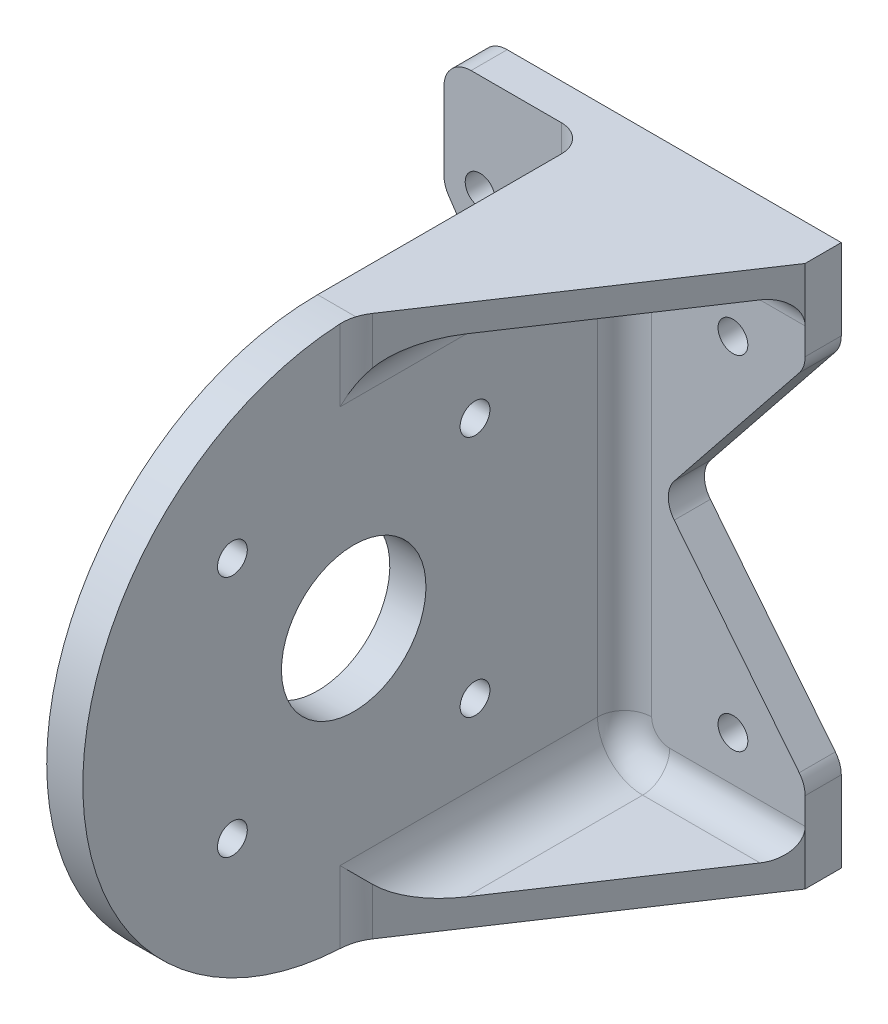
SolidWorks part; units mm, degrees
ref_plane "前视基准面" through (0, 0, 0) normal (0, 0, 1) x (1, 0, 0)
ref_plane "上视基准面" through (0, 0, 0) normal (0, 1, 0) x (1, 0, 0)
ref_plane "右视基准面" through (0, 0, 0) normal (1, 0, 0) x (0, 0, -1)
sketch "草图3" plane through (0, 0, 0) normal (0, 0, 1) x (1, 0, 0)
  line L6 (10, -30) -> (-10, -30)
  line L7 (10, -30) -> (10, 30)
  line L8 (10, 30) -> (-10, 30)
  line L9 (-10, -30) -> (-10, 30)
  line L10 (0, 30) -> (0, -30) construction
  line L11 (10, 0) -> (-10, 0) construction
  point P0 (0, 0)
  dimension "D1" = 20
  dimension "D2" = 60
extrude "凸台-拉伸2" add sketch "草图3" along normal blind 4 separate body
sketch "草图4" plane through (10, 0, 0) normal (1, 0, 0) x (0, 0, -1)
  line L0 (0, 30) -> (-34, 30)
  line L1 (0, -30) -> (-34, -30)
  line L2 (0, -30) -> (0, 30) construction
  line L3 (0, -30) -> (0, 30)
  line L4 (-34, 70) -> (-34, -49930) construction
  line L5 (-39, 0) -> (-50039, 0) construction
  line L7 (-47.435, 13.435) -> (-20.565, 13.435) construction
  line L8 (-47.435, 13.435) -> (-47.435, -13.435) construction
  line L9 (-47.435, -13.435) -> (-20.565, -13.435) construction
  line L10 (-20.565, 13.435) -> (-20.565, -13.435) construction
  line L11 (-34, -13.435) -> (-34, 13.435) construction
  line L12 (-47.435, 0) -> (-20.565, 0) construction
  arc A0 (-34, 30) -> (-34, -30) centre (-34, 0) ccw
  circle A1 centre (-34, 0) radius 8
  circle A2 centre (-47.435, 13.435) radius 1.65
  circle A3 centre (-20.565, 13.435) radius 1.65
  circle A4 centre (-20.565, -13.435) radius 1.65
  circle A5 centre (-47.435, -13.435) radius 1.65
  point P11 (-64, 0)
  dimension "D2" = 16
  dimension "D3" = 3.3
  dimension "D1" = 34
  dimension "D4" = 38
extrude "凸台-拉伸3" add sketch "草图4" against normal blind 4
sketch "草图9" plane through (0, 0, 0) normal (0, 0, 1) x (1, 0, 0)
  line L0 (10, -30) -> (10, 30) construction
  line L1 (10, 30) -> (30, 30)
  line L2 (10, 30) -> (10, -30)
  line L3 (10, -30) -> (30, -30)
  line L4 (30, 30) -> (30, -30)
  line L5 (6, 30) -> (-10, 30) construction
  line L6 (-10, -30) -> (6, -30) construction
  dimension "D1" = 20
extrude "凸台-拉伸6" add sketch "草图9" along normal up to surface (4 mm away) up to face at (-2, 0, 4)
sketch "草图5" plane through (0, 30, 0) normal (0, 1, 0) x (1, 0, 0)
  line L5 (10, -34) -> (30, -4)
  line L8 (10, -34) -> (10, -4) construction
  line L9 (30, -4) -> (10, -4) construction
  line L10 (10, -34) -> (10, -4)
  line L11 (30, -4) -> (10, -4)
extrude "凸台-拉伸4" add sketch "草图5" against normal blind 3
sketch "草图11" plane through (0, -30, 0) normal (0, -1, 0) x (1, 0, 0)
  line L3 (10, 34) -> (10, 4)
  line L4 (10, 4) -> (30, 4)
  line L5 (30, 4) -> (10, 34)
  line L6 (10, 34) -> (10, 4)
  line L7 (10, 4) -> (30, 4)
  line L8 (30, 4) -> (10, 34)
  dimension "D1" = 0
extrude "凸台-拉伸7" add sketch "草图11" against normal blind 3
sketch "草图7" plane through (0, 0, 4) normal (0, 0, 1) x (1, 0, 0)
  line L0 (6, -30) -> (6, 30) construction
  line L3 (22, 19) -> (30, 19) construction
  line L6 (10, -30) -> (10, 30) construction
  line L14 (-6, -19) -> (22, -19) construction
  line L15 (-6, -19) -> (-6, 19) construction
  line L16 (-6, 19) -> (22, 19) construction
  line L17 (22, -19) -> (22, 19) construction
  line L18 (8, 19) -> (8, -19) construction
  line L19 (-6, 0) -> (22, 0) construction
  line L20 (30, 19) -> (30, -19) construction
  line L21 (30, -19) -> (22, -19) construction
  line L22 (-10, 30) -> (-10, -30) construction
  line L24 (-10, 17.5) -> (2, 0)
  line L25 (2, 0) -> (-10, -17.5)
  line L26 (-10, -17.5) -> (-10, 17.5)
  line L27 (14, 0) -> (30, 20)
  line L28 (30, -27) -> (30, 27) construction
  line L29 (30, 20) -> (30, -20)
  line L30 (30, -20) -> (14, 0)
  circle A0 centre (-6, 19) radius 1.65
  circle A1 centre (22, 19) radius 1.65
  circle A4 centre (22, -19) radius 1.65
  circle A5 centre (-6, -19) radius 1.65
  point P0 (8, 0)
  point P18 (13.7409, 0)
  dimension "D1" = 3.3
  dimension "D2" = 4
  dimension "D3" = 35
  dimension "D4" = 38
  dimension "D5" = 36
  dimension "D6" = 8
  dimension "D7" = 4
  dimension "D8" = 4
  dimension "D9" = 40
extrude "切除-拉伸1" cut sketch "草图7" against normal through all
fillet "圆角1" radius 5 4 edges at (10, 27, 19) (10, 28.5, 34) (10, -28.5, 34) (10, -27, 19)
fillet "圆角2" radius 3 11 edges at (22.5, 27, 4) (11.4645, 25.5355, 4) (10, 0, 4) (30, 20, 2) (30, -20, 2) (14, 0, 2) (-10, -17.5, 2) (2, 0, 2) (-10, 17.5, 2) (11.4645, -25.5355, 4) (22.5, -27, 4)
fillet "圆角3" radius 3 3 edges at (-10, 30, 2) (-10, -30, 2) (6, 0, 4)
